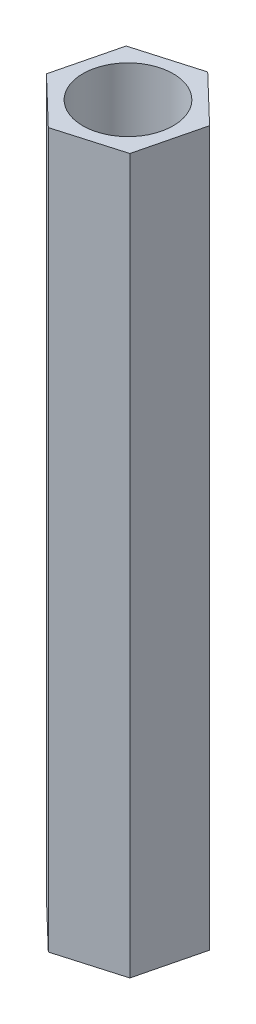
SolidWorks part; units mm, degrees
ref_plane "Front Plane" through (0, 0, 0) normal (0, 0, 1) x (1, 0, 0)
ref_plane "Top Plane" through (0, 0, 0) normal (0, 1, 0) x (1, 0, 0)
ref_plane "Right Plane" through (0, 0, 0) normal (1, 0, 0) x (0, 0, -1)
sketch "Sketch1" plane through (0, 0, 0) normal (0, 1, 0) x (1, 0, 0)
  line L1 (1.83, 0.5303) -> (0.4557, 1.85)
  line L2 (0.4557, 1.85) -> (-1.3743, 1.3196)
  line L3 (-1.3743, 1.3196) -> (-1.83, -0.5303)
  line L4 (-1.83, -0.5303) -> (-0.4557, -1.85)
  line L5 (-0.4557, -1.85) -> (1.3743, -1.3196)
  line L6 (1.3743, -1.3196) -> (1.83, 0.5303)
  circle A0 centre (0, 0) radius 1.65 construction
  dimension "D1" = 3.3
extrude "Boss-Extrude1" add sketch "Sketch1" along normal blind 20.66
sketch "Sketch2" plane through (0, 20.66, 0) normal (0, 1, 0) x (1, 0, 0)
  circle A0 centre (0, 0) radius 1.3078
extrude "Cut-Extrude1" cut sketch "Sketch2" against normal blind 20.66
